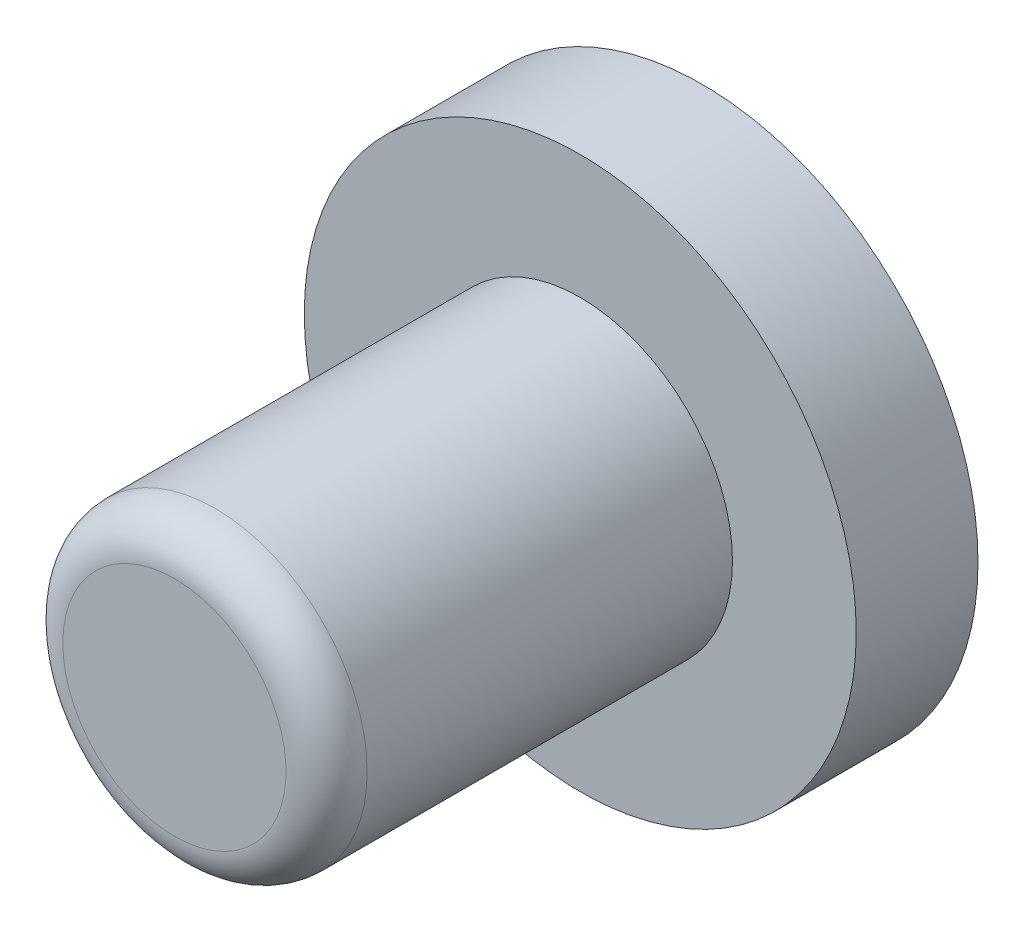
SolidWorks part; units mm, degrees
material "Alloy Steel"
ref_plane "Front Plane" through (0, 0, 0) normal (0, 0, 1) x (1, 0, 0)
ref_plane "Top Plane" through (0, 0, 0) normal (0, 1, 0) x (1, 0, 0)
ref_plane "Right Plane" through (0, 0, 0) normal (1, 0, 0) x (0, 0, -1)
sketch "Sketch1" plane through (0, 0, 0) normal (1, 0, 0) x (0, 0, -1)
  line L0 (-51.4865, 0) -> (51.4865, 0) construction
  line L1 (16.51, 0) -> (16.51, 17.272)
  line L2 (16.51, 17.272) -> (8.89, 17.272)
  line L3 (8.89, 17.272) -> (8.89, 9.525)
  line L4 (8.89, 9.525) -> (-16.51, 9.525)
  line L5 (-16.51, 9.525) -> (-16.51, 0)
  line L6 (16.51, 0) -> (-16.51, 0)
  point P4 (0, 0)
  dimension "D1" = 9.525
  dimension "D2" = 17.272
  dimension "D3" = 25.4
  dimension "D4" = 33.02
  dimension "D5" = 16.51
revolve "Revolve1" add sketch "Sketch1" angle 360 about L0
fillet "Fillet1" radius 2.54 1 edges at (9.525, 0, 16.51)
